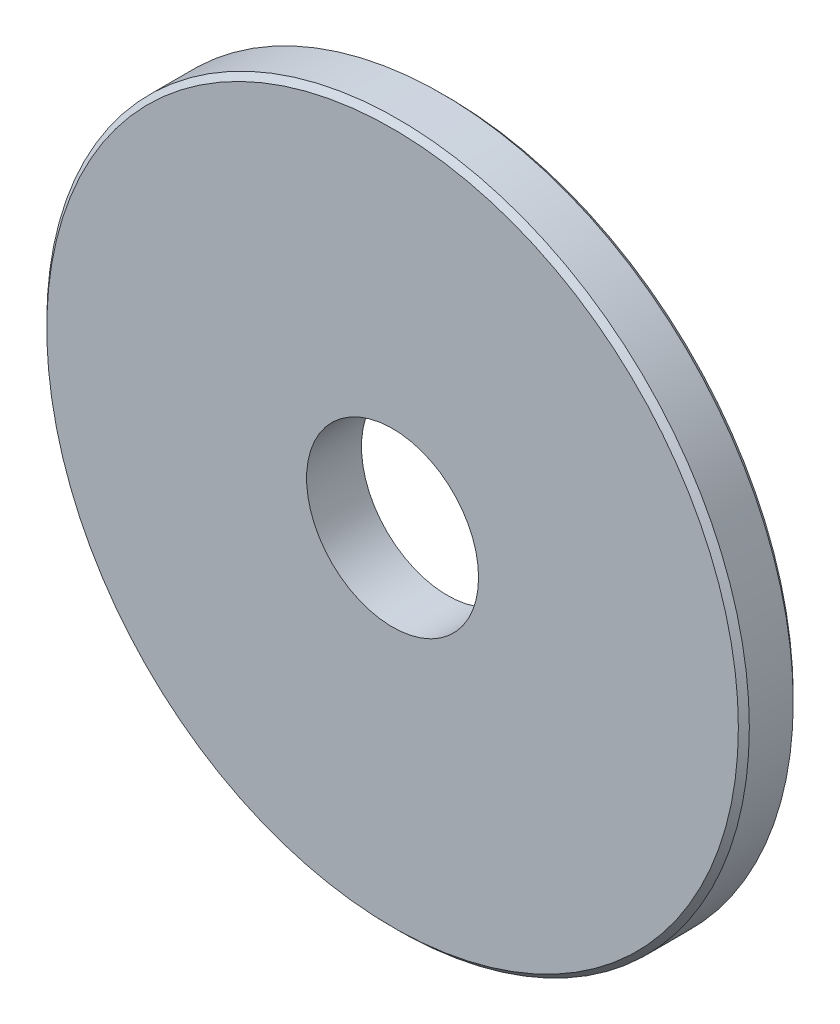
SolidWorks part; units mm, degrees
material "1060 Alloy"
ref_plane "Front Plane" through (0, 0, 0) normal (0, 0, 1) x (1, 0, 0)
ref_plane "Top Plane" through (0, 0, 0) normal (0, 1, 0) x (1, 0, 0)
ref_plane "Right Plane" through (0, 0, 0) normal (1, 0, 0) x (0, 0, -1)
sketch "Sketch1" plane through (0, 0, 0) normal (0, 0, 1) x (1, 0, 0)
  circle A0 centre (0, 0) radius 64.016
  circle A1 centre (0, 0) radius 15.6726
extrude "Boss-Extrude1" add sketch "Sketch1" along normal blind 10
chamfer "Chamfer1" distance 1 angle 45 2 edges at (64.016, 0, 0) (64.016, 0, 10)
